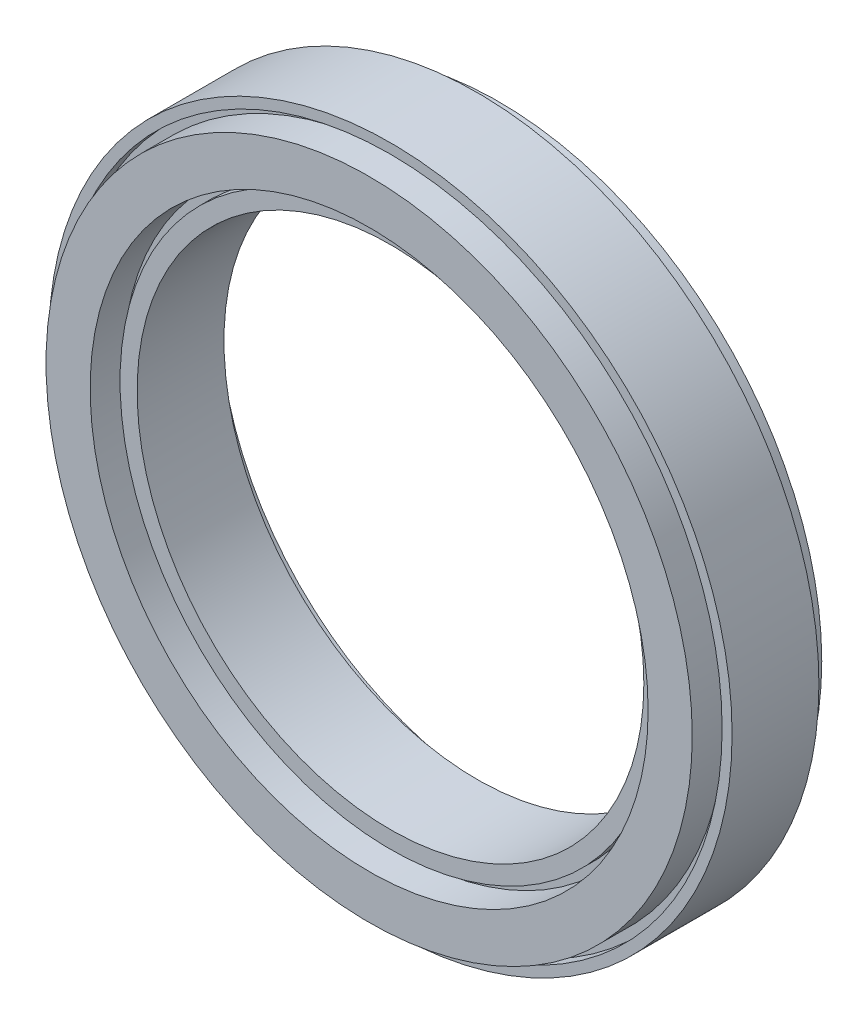
SolidWorks part; units mm, degrees
material "Chrome Stainless Steel"
ref_plane "Front Plane" through (0, 0, 0) normal (0, 0, 1) x (1, 0, 0)
ref_plane "Top Plane" through (0, 0, 0) normal (0, 1, 0) x (1, 0, 0)
ref_plane "Right Plane" through (0, 0, 0) normal (1, 0, 0) x (0, 0, -1)
sketch "Sketch1" plane through (0, 0, 0) normal (0, 0, 1) x (1, 0, 0)
  circle A0 centre (0, 0) radius 24
  circle A1 centre (0, 0) radius 17.8
  dimension "D1" = 48
  dimension "D2" = 35.6
extrude "Boss-Extrude1" add sketch "Sketch1" along normal mid plane 6.1
sketch "Sketch2" plane through (0, 0, 3.05) normal (0, 0, 1) x (1, 0, 0)
  circle A0 centre (0, 0) radius 19
  circle A1 centre (0, 0) radius 23.3
  dimension "D1" = 46.6
  dimension "D2" = 38
extrude "Cut-Extrude1" cut sketch "Sketch2" against normal blind 0.8
sketch "Sketch3" plane through (0, 0, 2.25) normal (0, 0, 1) x (1, 0, 0)
  circle A0 centre (0, 0) radius 19.6
  circle A1 centre (0, 0) radius 22.7
  dimension "D1" = 39.2
  dimension "D2" = 45.4
extrude "Boss-Extrude2" add sketch "Sketch3" along normal blind 2.3
mirror "Mirror1" about plane through (0, 0, 0) normal (0, 0, 1) of "Cut-Extrude1", "Boss-Extrude2"
